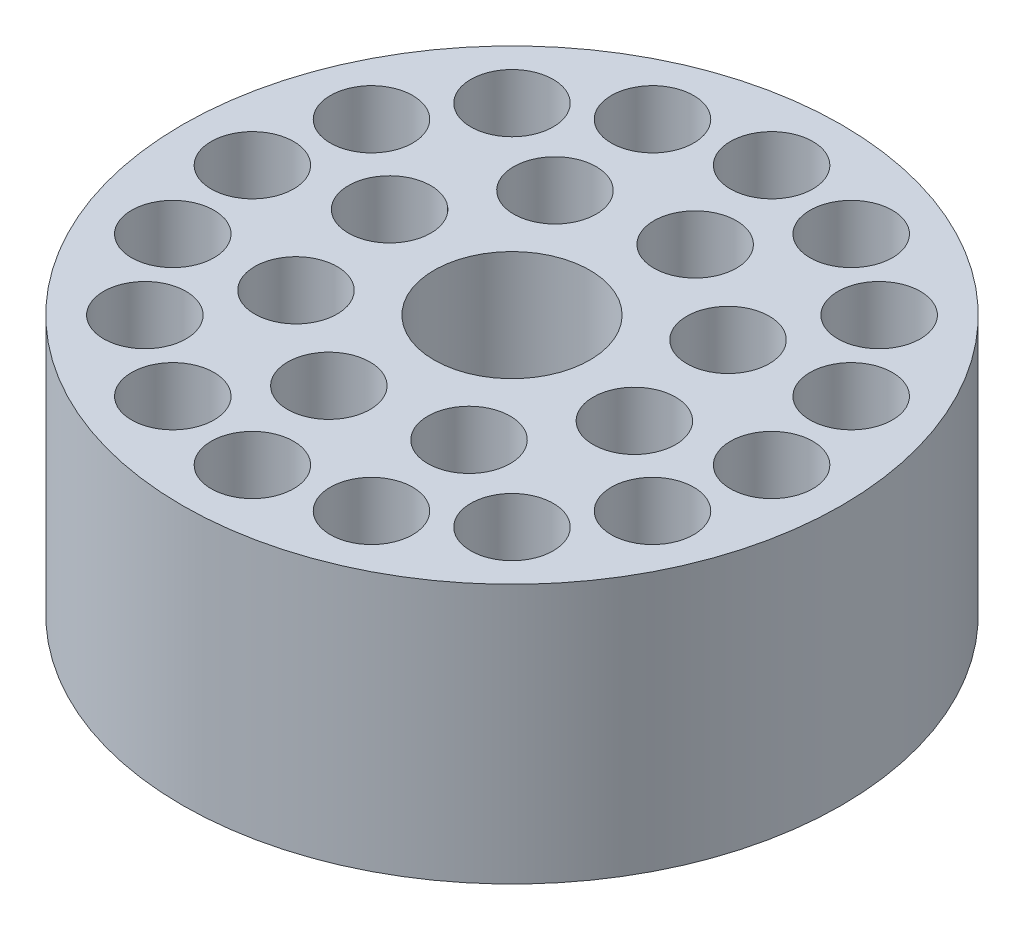
SolidWorks part; units mm, degrees
ref_plane "Front Plane" through (0, 0, 0) normal (0, 0, 1) x (1, 0, 0)
ref_plane "Top Plane" through (0, 0, 0) normal (0, 1, 0) x (1, 0, 0)
ref_plane "Right Plane" through (0, 0, 0) normal (1, 0, 0) x (0, 0, -1)
sketch "Sketch1" plane through (0, 0, 0) normal (0, 1, 0) x (1, 0, 0)
  circle A0 centre (0, 0) radius 6.35
  dimension "D1" = 12.7
extrude "Boss-Extrude1" add sketch "Sketch1" along normal blind 5
sketch "Sketch2" plane through (0, 5, 0) normal (0, 1, 0) x (1, 0, 0)
  circle A0 centre (0, 5) radius 0.7938
  dimension "D1" = 1.5875
  dimension "D2" = 5
extrude "Cut-Extrude1" cut sketch "Sketch2" against normal through all
pattern_circular "CirPattern1" count 16 over 360 about axis through (0, 0, 0) along (0, 1, 0) of "Cut-Extrude1"
sketch "Sketch3" plane through (0, 5, 0) normal (0, 1, 0) x (1, 0, 0)
  line L0 (0, 5) -> (1.9134, 4.6194) construction
  line L1 (0.9567, 4.8097) -> (0, 0) construction
  circle A3 centre (0.5853, 2.9424) radius 0.7938
  dimension "D1" = 3
extrude "Cut-Extrude2" cut sketch "Sketch3" against normal through all
pattern_circular "CirPattern3" count 8 over 360 about axis through (0, 0, 0) along (0, 1, 0) of "Cut-Extrude2"
sketch "Sketch4" plane through (0, 5, 0) normal (0, 1, 0) x (1, 0, 0)
  circle A0 centre (0, 0) radius 1.5
  dimension "D1" = 3
extrude "Cut-Extrude3" cut sketch "Sketch4" against normal through all
